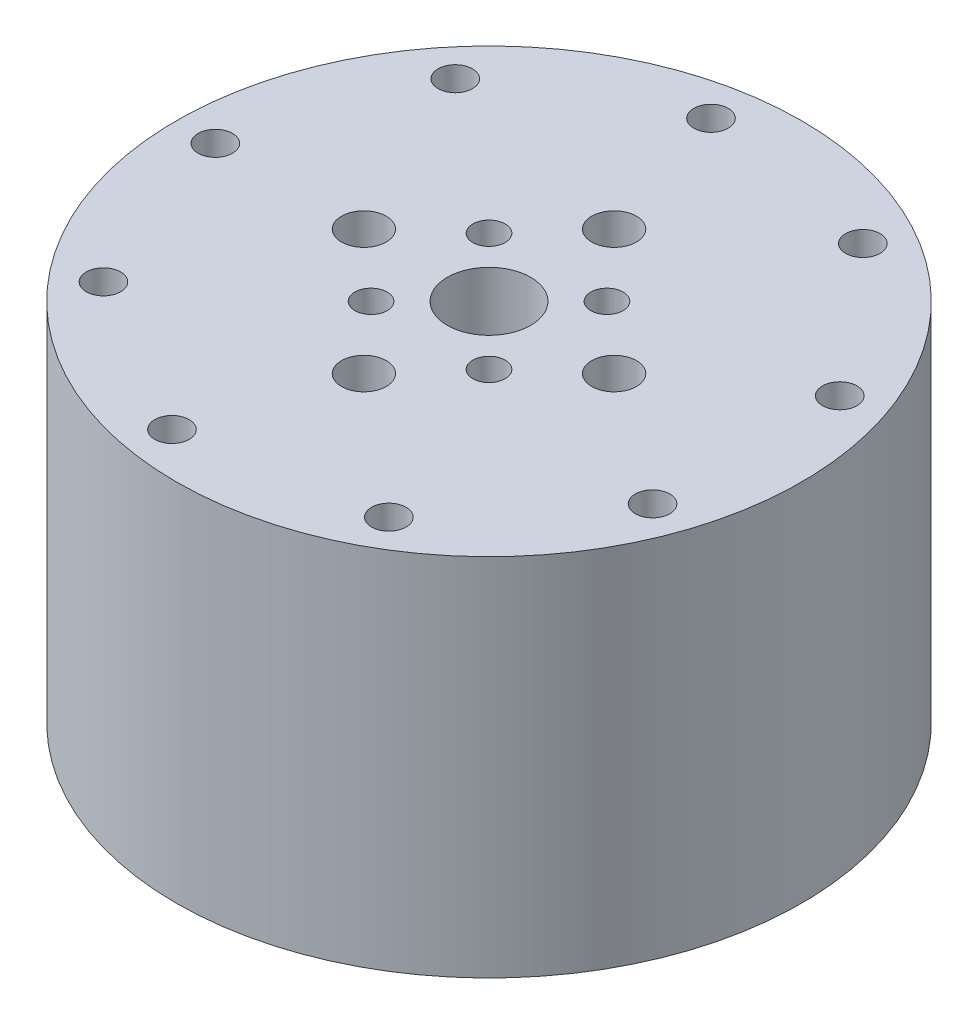
SolidWorks part; units mm, degrees
ref_plane "前视基准面" through (0, 0, 0) normal (0, 0, 1) x (1, 0, 0)
ref_plane "上视基准面" through (0, 0, 0) normal (0, 1, 0) x (1, 0, 0)
ref_plane "右视基准面" through (0, 0, 0) normal (1, 0, 0) x (0, 0, -1)
sketch "草图1" plane through (0, 0, 0) normal (0, 1, 0) x (1, 0, 0)
  circle A0 centre (0, 0) radius 30
extrude "凸台-拉伸1" add sketch "草图1" along normal blind 35
sketch3d "3D草图1"
  line L0 (-71.4046, 17.5, 0) -> (71.4046, 17.5, 0)
  line L1 (0, 17.5, 0) -> (-50, 17.5, 0)
  point P0 (0, 17.5, 0)
  point P4 (0, 17.5, 0)
  point P5 (0, 17.5, 0)
sketch "草图2" plane through (0, 0, 0) normal (0, -1, 0) x (1, 0, 0)
  circle A1 centre (-26.25, 0) radius 1.65
  circle A2 centre (-20.1087, 16.8732) radius 1.65
  circle A3 centre (-4.5583, 25.8512) radius 1.65
  circle A4 centre (13.125, 22.7332) radius 1.65
  circle A5 centre (24.6669, 8.978) radius 1.65
  circle A6 centre (24.6669, -8.978) radius 1.65
  circle A7 centre (13.125, -22.7332) radius 1.65
  circle A8 centre (-4.5583, -25.8512) radius 1.65
  circle A9 centre (-20.1087, -16.8732) radius 1.65
  point P24 (0, 0)
  dimension "D1" = 9
extrude "切除-拉伸1" cut sketch "草图2" against normal through all
sketch "草图4" plane through (0, 0, 0) normal (0, -1, 0) x (1, 0, 0)
  circle A0 centre (0, 0) radius 20
extrude "切除-拉伸3" cut sketch "草图4" against normal blind 10
sketch "草图5" plane through (0, 10, 0) normal (0, -1, 0) x (1, 0, 0)
  circle A0 centre (0, 0) radius 4
extrude "切除-拉伸4" cut sketch "草图5" against normal through all
sketch "草图6" plane through (0, 10, 0) normal (0, -1, 0) x (1, 0, 0)
  circle A9 centre (0, 12) radius 2.15
  circle A10 centre (12, 0) radius 2.15
  circle A11 centre (0, -12) radius 2.15
  circle A12 centre (-12, 0) radius 2.15
  circle A14 centre (-5.6569, -5.6569) radius 1.55
  circle A15 centre (-5.6569, 5.6569) radius 1.55
  circle A16 centre (5.6569, 5.6569) radius 1.55
  circle A17 centre (5.6569, -5.6569) radius 1.55
  point P11 (0, 0)
  point P12 (0, 0)
  point P18 (0, 0)
  point P22 (0, 0)
  point P25 (0, 0)
  dimension "D1" = 4
  dimension "D2" = 4
extrude "切除-拉伸5" cut sketch "草图6" against normal through all
